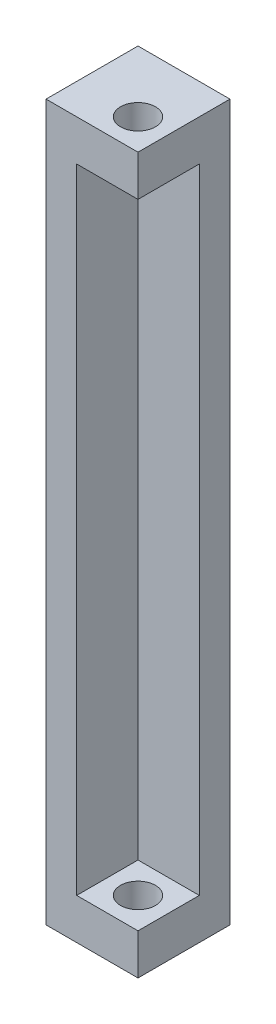
SolidWorks part; units mm, degrees
ref_plane "Front Plane" through (0, 0, 0) normal (0, 0, 1) x (1, 0, 0)
ref_plane "Top Plane" through (0, 0, 0) normal (0, 1, 0) x (1, 0, 0)
ref_plane "Right Plane" through (0, 0, 0) normal (1, 0, 0) x (0, 0, -1)
sketch "Sketch2" plane through (0, 0, 0) normal (0, 1, 0) x (1, 0, 0)
  line L1 (-1.2818, 0.3734) -> (10.1482, 0.3734)
  line L2 (-1.2818, 0.3734) -> (-1.2818, -11.0566)
  line L3 (-1.2818, -11.0566) -> (10.1482, -11.0566)
  line L4 (10.1482, 0.3734) -> (10.1482, -11.0566)
  dimension "D1" = 11.43
  dimension "D2" = 11.43
extrude "Boss-Extrude1" add sketch "Sketch2" along normal blind 5.08
sketch "Sketch3" plane through (0, 5.08, 0) normal (0, 1, 0) x (1, 0, 0)
  line L0 (-1.2818, -11.0566) -> (10.1482, -11.0566) construction
  line L1 (2.5282, -11.0566) -> (-1.2818, -11.0566)
  line L2 (2.5282, -11.0566) -> (2.5282, -3.4366)
  line L3 (2.5282, 0.3734) -> (-1.2818, 0.3734)
  line L4 (-1.2818, -11.0566) -> (-1.2818, 0.3734)
  line L5 (10.1482, -11.0566) -> (10.1482, 0.3734) construction
  line L6 (-1.2818, 0.3734) -> (10.1482, 0.3734)
  line L7 (-1.2818, 0.3734) -> (-1.2818, -3.4366)
  line L8 (2.5282, -3.4366) -> (10.1482, -3.4366)
  line L9 (10.1482, 0.3734) -> (10.1482, -3.4366)
  line M4 (-1.2818, 0.3734) -> (-1.2818, -11.0566)
  line M5 (-1.2818, -11.0566) -> (10.1482, -11.0566)
  line M6 (10.1482, -11.0566) -> (10.1482, 0.3734)
  line M7 (10.1482, 0.3734) -> (-1.2818, 0.3734)
  dimension "D1" = 3.81
  dimension "D2" = 3.81
extrude "Boss-Extrude2" add sketch "Sketch3" along normal blind 83.82 contours L2 L8 L4 M6 M7 M4 M5
sketch "Sketch4" plane through (2.5282, 0, 0) normal (1, 0, 0) x (0, 0, -1)
  line L0 (-3.4366, 88.9) -> (-3.4366, 5.08) construction
  line L1 (-11.0566, 88.9) -> (-3.4366, 88.9)
  line L2 (-11.0566, 88.9) -> (-11.0566, 83.82)
  line L3 (-11.0566, 83.82) -> (-3.4366, 83.82)
  line L4 (-3.4366, 88.9) -> (-3.4366, 83.82)
  dimension "D1" = 5.08
extrude "Boss-Extrude3" add sketch "Sketch4" along normal blind 7.62
sketch "Sketch5" plane through (0, 88.9, 0) normal (0, 1, 0) x (1, 0, 0)
  line L0 (10.1482, -11.0566) -> (10.1482, 0.3734) construction
  line L1 (-1.2818, -11.0566) -> (10.1482, -11.0566) construction
  circle A0 centre (6.3382, -7.2466) radius 2.1717
  dimension "D1" = 3.81
  dimension "D2" = 3.81
extrude "Cut-Extrude1" cut sketch "Sketch5" against normal blind 5.08
sketch "Sketch6" plane through (0, 5.08, 0) normal (0, 1, 0) x (1, 0, 0)
  line L0 (2.5282, -11.0566) -> (10.1482, -11.0566) construction
  line L1 (10.1482, -11.0566) -> (10.1482, -3.4366) construction
  circle A0 centre (6.3382, -7.2466) radius 2.1717
  dimension "D1" = 3.81
  dimension "D2" = 3.81
extrude "Cut-Extrude2" cut sketch "Sketch6" against normal blind 5.08
